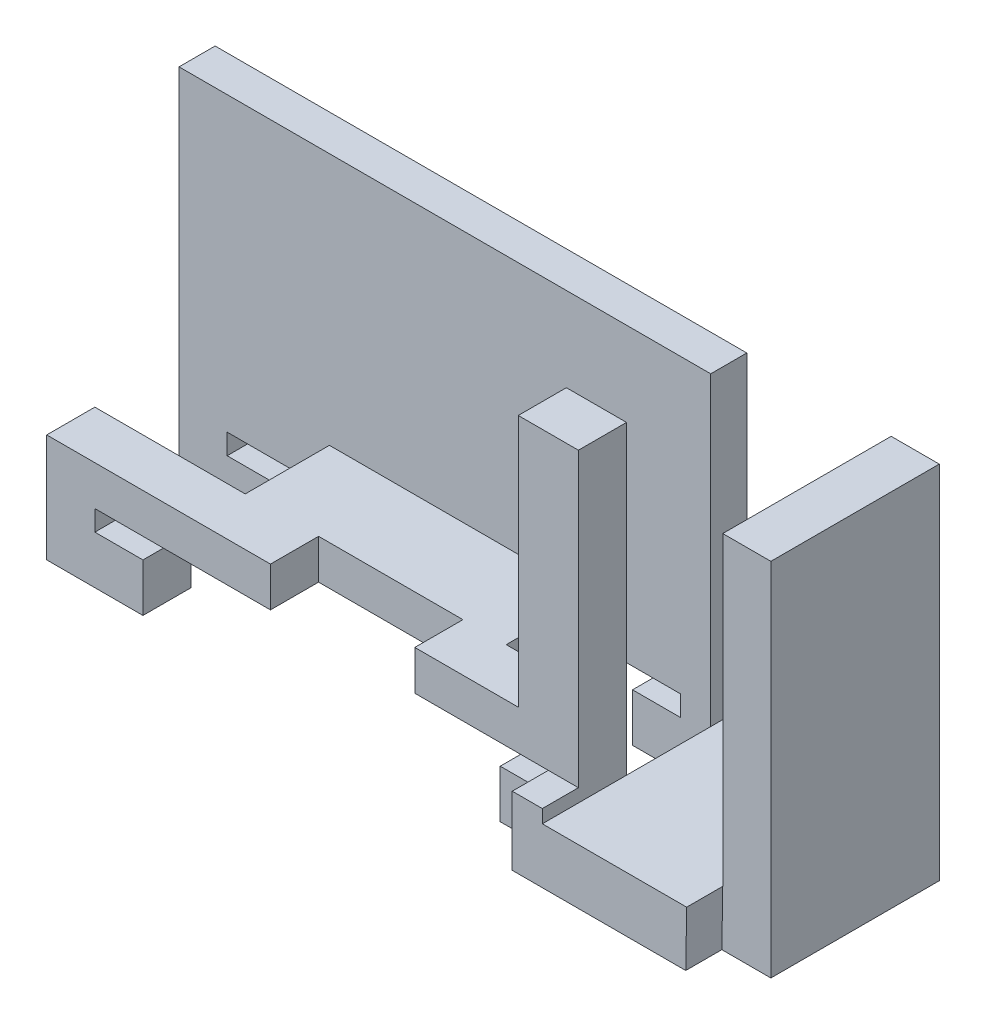
SolidWorks part; units mm, degrees
ref_plane "Alzado" through (0, 0, 0) normal (0, 0, 1) x (1, 0, 0)
ref_plane "Planta" through (0, 0, 0) normal (0, 1, 0) x (1, 0, 0)
ref_plane "Vista lateral" through (0, 0, 0) normal (1, 0, 0) x (0, 0, -1)
sketch "Croquis1" plane through (0, 0, 0) normal (0, 1, 0) x (1, 0, 0)
  line L1 (-56.1237, 20.1765) -> (4.0763, 20.1765)
  line L2 (-56.1237, 20.1765) -> (-56.1237, 6.1765)
  line L3 (-56.1237, 6.1765) -> (4.0763, 6.1765)
  line L4 (4.0763, 20.1765) -> (4.0763, 6.1765)
  dimension "D1" = 14
  dimension "D2" = 60.2
extrude "Saliente-Extruir1" add sketch "Croquis1" along normal blind 30
sketch "Croquis2" plane through (0, 0, -6.1765) normal (0, 0, 1) x (1, 0, 0)
  line L0 (-56.1237, 0) -> (4.0763, 0) construction
  line L1 (-48.1237, 0) -> (-18.4237, 0)
  line L2 (-48.1237, 4) -> (-48.1237, 0)
  line L3 (-50.0237, 5.7) -> (-19.0237, 5.7)
  line L4 (-18.4237, 4) -> (-18.4237, 0)
  line L5 (-56.1237, 30) -> (-56.1237, 0) construction
  line L10 (-52.1237, 5.7) -> (-50.0237, 5.7)
  line L11 (-52.1237, 5.7) -> (-52.1237, 4)
  line L12 (-52.1237, 4) -> (-48.1237, 4)
  line L13 (-56.1237, 30) -> (4.0763, 30) construction
  line L14 (-19.0237, 5.7) -> (-14.4237, 5.7)
  line L15 (-11.9237, 4.6) -> (0.0763, 4.6)
  line L16 (-18.4237, 4) -> (-14.4237, 4)
  line L17 (-14.4237, 5.7) -> (-14.4237, 4)
  line L18 (-11.9237, 4.6) -> (-11.9237, 30)
  line L19 (-11.9237, 30) -> (0.0763, 30)
  line L20 (0.0763, 4.6) -> (0.0763, 30)
  dimension "D2" = 37.7
  dimension "D3" = 4
  dimension "D4" = 4
  dimension "D5" = 4
  dimension "D6" = 4
  dimension "D7" = 4
  dimension "D9" = 4
  dimension "D10" = 12
extrude "Cortar-Extruir1" cut sketch "Croquis2" against normal up to vertex (14 mm away)
sketch "Croquis3" plane through (0, 30, 0) normal (0, 1, 0) x (1, 0, 0)
  line L0 (-56.1237, 20.1765) -> (-56.1237, 6.1765) construction
  line L1 (-56.1237, 17.1765) -> (-43.6237, 17.1765)
  line L2 (-56.1237, 17.1765) -> (-56.1237, 10.1765)
  line L3 (-56.1237, 10.1765) -> (-43.6237, 10.1765)
  line L4 (-43.6237, 17.1765) -> (-43.6237, 10.1765)
  line L5 (-11.9237, 20.1765) -> (-11.9237, 6.1765) construction
  line L6 (-11.9237, 17.1765) -> (-21.9237, 17.1765)
  line L7 (-11.9237, 17.1765) -> (-11.9237, 10.1765)
  line L8 (-11.9237, 10.1765) -> (-21.9237, 10.1765)
  line L9 (-21.9237, 17.1765) -> (-21.9237, 10.1765)
  dimension "D1" = 3
  dimension "D2" = 7
  dimension "D3" = 12.5
  dimension "D4" = 3
  dimension "D5" = 10
  dimension "D6" = 7
extrude "Cortar-Extruir2" cut sketch "Croquis3" against normal up to vertex
sketch "Croquis4" plane through (0, 30, 0) normal (0, 1, 0) x (1, 0, 0)
  line L0 (-43.6237, 17.1765) -> (-21.9237, 17.1765)
  line L1 (-21.9237, 17.1765) -> (-21.9237, 10.1765)
  line L2 (-21.9237, 10.1765) -> (-16.9237, 10.1765)
  line L3 (-21.9237, 10.1765) -> (-11.9237, 10.1765) construction
  line L4 (-16.9237, 6.1765) -> (-56.1237, 6.1765)
  line L5 (-56.1237, 6.1765) -> (-56.1237, 10.1765)
  line L6 (-56.1237, 10.1765) -> (-43.6237, 10.1765)
  line L7 (-43.6237, 10.1765) -> (-43.6237, 17.1765)
  line L8 (-16.9237, 10.1765) -> (-16.9237, 6.1765)
extrude "Cortar-Extruir3" cut sketch "Croquis4" against normal blind 21
sketch "Croquis5" plane through (0, 9, 0) normal (0, 1, 0) x (1, 0, 0)
  line L0 (-56.1237, 6.1765) -> (-16.9237, 6.1765) construction
  line L1 (-37.5237, 6.1765) -> (-25.5237, 6.1765)
  line L2 (-37.5237, 6.1765) -> (-37.5237, 10.1765)
  line L3 (-37.5237, 10.1765) -> (-25.5237, 10.1765)
  line L4 (-25.5237, 6.1765) -> (-25.5237, 10.1765)
  line L5 (-43.6237, 17.1765) -> (-43.6237, 10.1765) construction
  dimension "D1" = 12
  dimension "D2" = 4
  dimension "D3" = 6.1
extrude "Cortar-Extruir4" cut sketch "Croquis5" against normal up to vertex (3.3 mm away)
sketch "Croquis6" plane through (0, 0, -6.1765) normal (0, 0, 1) x (1, 0, 0)
  line L0 (-14.4237, 5.7) -> (-11.9237, 5.7)
  line L1 (-11.9237, 30) -> (-11.9237, 4.6) construction
  line L2 (-11.9237, 5.7) -> (-11.9237, 4.6)
  line L3 (-11.9237, 4.6) -> (0.0763, 4.6)
  line L4 (0.0763, 4.6) -> (0, 0)
  line L5 (0, 0) -> (-14.4237, 0)
  line L6 (-18.4237, 0) -> (4.0763, 0) construction
  line L7 (-14.4237, 0) -> (-14.4237, 5.7)
extrude "Saliente-Extruir2" add sketch "Croquis6" along normal blind 3
sketch "Croquis7" plane through (0, 0, -20.1765) normal (0, 0, -1) x (-1, 0, 0)
  line L0 (14.4237, 5.7) -> (11.9237, 5.7)
  line L1 (11.9237, 30) -> (11.9237, 4.6) construction
  line L2 (11.9237, 5.7) -> (11.9237, 4.6)
  line L3 (11.9237, 4.6) -> (-0.0763, 4.6)
  line L4 (-0.0763, 4.6) -> (0, 0)
  line L5 (0, 0) -> (14.4237, 0)
  line L6 (-4.0763, 0) -> (18.4237, 0) construction
  line L7 (14.4237, 0) -> (14.4237, 5.7)
extrude "Saliente-Extruir3" add sketch "Croquis7" along normal blind 3
